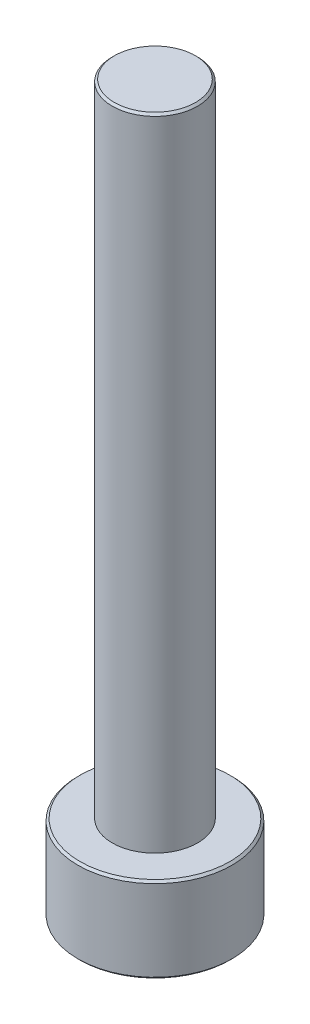
SolidWorks part; units mm, degrees
material "Q235"
ref_plane "前视基准面" through (0, 0, 0) normal (0, 0, 1) x (1, 0, 0)
ref_plane "上视基准面" through (0, 0, 0) normal (0, 1, 0) x (1, 0, 0)
ref_plane "右视基准面" through (0, 0, 0) normal (1, 0, 0) x (0, 0, -1)
sketch "草图1" plane through (0, 0, 0) normal (0, 1, 0) x (1, 0, 0)
  circle A0 centre (0, 0) radius 3.61
  dimension "D1" = 7.22
extrude "杯头部分" add sketch "草图1" along normal blind 4
sketch "草图2" plane through (0, 4, 0) normal (0, 1, 0) x (1, 0, 0)
  circle A0 centre (0, 0) radius 2
  dimension "D1" = 4
extrude "螺柱部分" add sketch "草图2" along normal blind 30
cosmetic thread "装饰螺纹线1" parameters "D2"=2.459
sketch "草图3" plane through (0, 0, 0) normal (0, -1, 0) x (1, 0, 0)
  line L1 (1.54, -0.8891) -> (1.54, 0.8891)
  line L2 (1.54, 0.8891) -> (0, 1.7782)
  line L3 (0, 1.7782) -> (-1.54, 0.8891)
  line L4 (-1.54, 0.8891) -> (-1.54, -0.8891)
  line L5 (-1.54, -0.8891) -> (0, -1.7782)
  line L6 (0, -1.7782) -> (1.54, -0.8891)
  circle A0 centre (0, 0) radius 1.54 construction
  dimension "D1" = 3.08
extrude "沉头内六角" cut sketch "草图3" against normal blind 2
chamfer "修饰性倒角" distance 0.1 angle 45 3 edges at (0, 34, 2) (0, 4, 3.61) (0, 0, 3.61)
